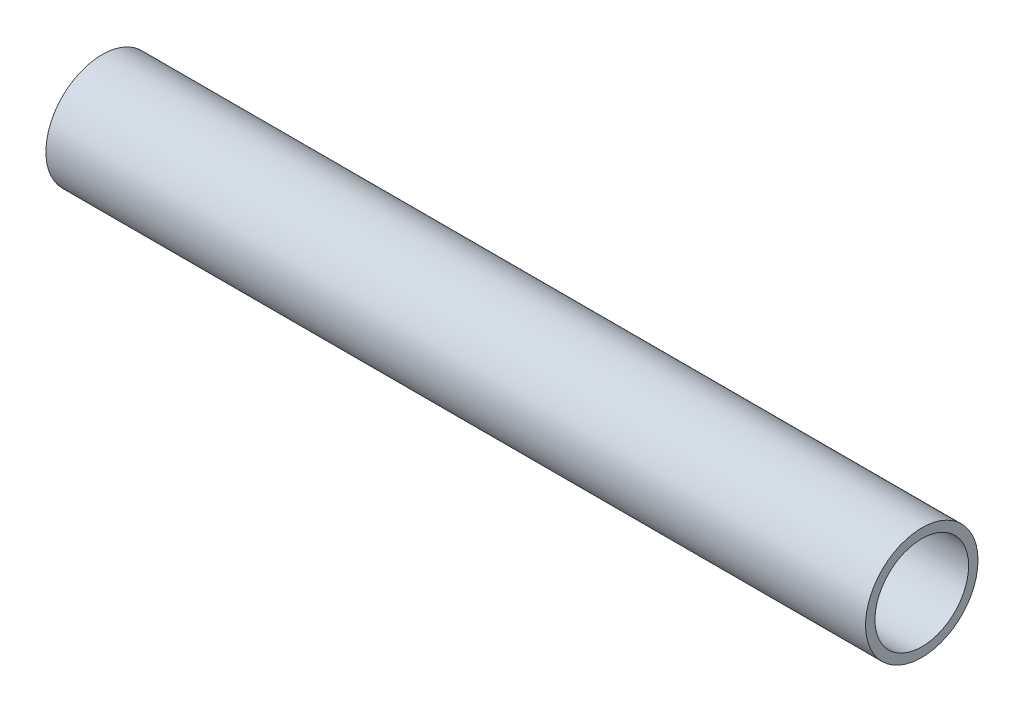
SolidWorks part; units mm, degrees
ref_plane "Front Plane" through (0, 0, 0) normal (0, 0, 1) x (1, 0, 0)
ref_plane "Top Plane" through (0, 0, 0) normal (0, 1, 0) x (1, 0, 0)
ref_plane "Right Plane" through (0, 0, 0) normal (1, 0, 0) x (0, 0, -1)
sketch "Sketch1" plane through (0, 0, 0) normal (1, 0, 0) x (0, 0, -1)
  circle A0 centre (0, 0) radius 2.4
  circle A1 centre (0, 0) radius 2
  dimension "D1" = 4
  dimension "D2" = 0.4
extrude "Boss-Extrude1" add sketch "Sketch1" along normal blind 35
